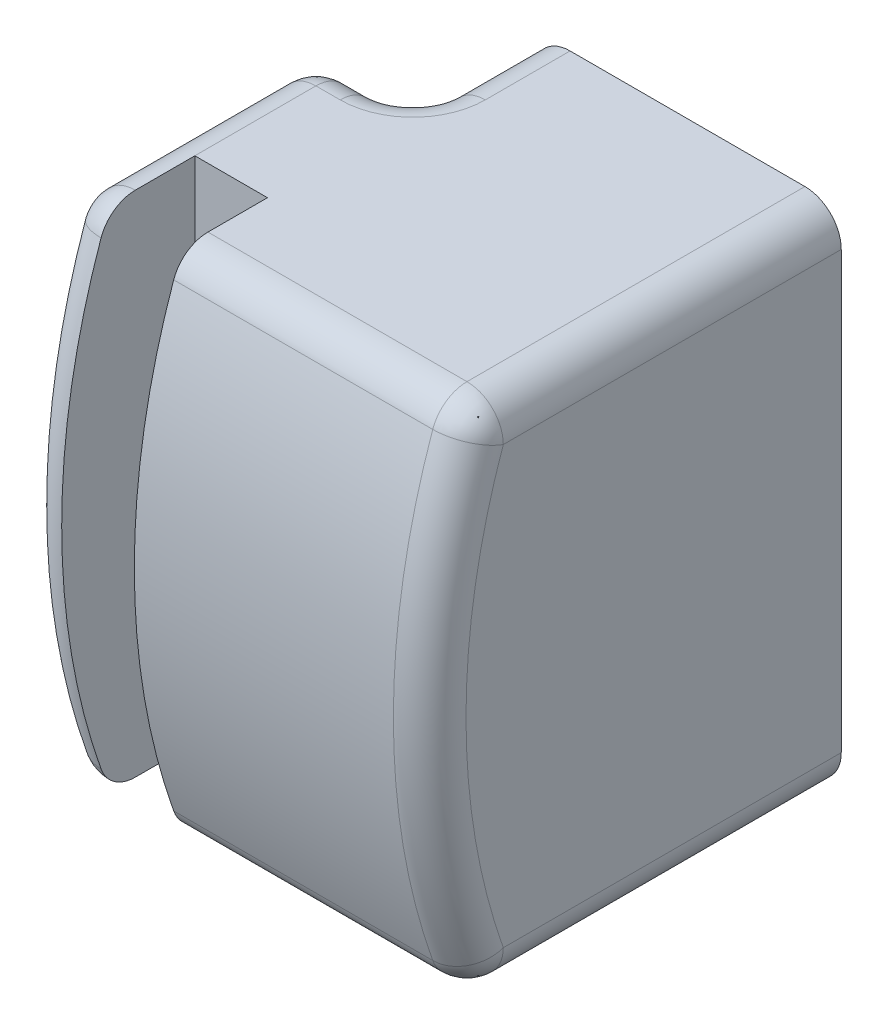
SolidWorks part; units mm, degrees
ref_plane "Alzado" through (0, 0, 0) normal (0, 0, 1) x (1, 0, 0)
ref_plane "Planta" through (0, 0, 0) normal (0, 1, 0) x (1, 0, 0)
ref_plane "Vista lateral" through (0, 0, 0) normal (1, 0, 0) x (0, 0, -1)
sketch "Croquis1" plane through (0, 0, 0) normal (0, 0, 1) x (1, 0, 0)
  line L1 (-58.5, 100) -> (58.5, 100)
  line L2 (-58.5, 100) -> (-58.5, -100)
  line L3 (-58.5, -100) -> (58.5, -100)
  line L4 (58.5, 100) -> (58.5, -100)
  line L5 (-58.5, 100) -> (58.5, -100) construction
  line L6 (-58.5, -100) -> (58.5, 100) construction
  point P0 (0, 0)
  dimension "D1" = 200
  dimension "D2" = 117
extrude "Saliente-Extruir1" add sketch "Croquis1" along normal blind 5
sketch "Croquis2" plane through (0, 0, 5) normal (0, 0, 1) x (1, 0, 0)
  line L1 (-58.5, 100) -> (58.5, 100)
  line L2 (-58.5, 100) -> (-58.5, -100)
  line L3 (-58.5, -100) -> (58.5, -100)
  line L4 (58.5, 100) -> (58.5, -100)
  line L5 (-58.5, 100) -> (58.5, -100) construction
  line L6 (-58.5, -100) -> (58.5, 100) construction
  line L7 (-63.5, 105) -> (63.5, 105)
  line L8 (-63.5, 105) -> (-63.5, -105)
  line L9 (-63.5, -105) -> (63.5, -105)
  line L10 (63.5, 105) -> (63.5, -105)
  line L11 (-63.5, 105) -> (63.5, -105) construction
  line L12 (-63.5, -105) -> (63.5, 105) construction
  point P0 (0, 0)
  point P7 (0, 0)
  dimension "D1" = 5
  dimension "D2" = 5
extrude "Saliente-Extruir2" add sketch "Croquis2" against normal blind 150
sketch "Croquis3" plane through (-63.5, 0, 0) normal (-1, 0, 0) x (0, 0, 1)
  line L0 (5, 105) -> (5, -105)
  line L1 (5, -105) -> (-95, -105)
  line L2 (-145, -105) -> (5, -105) construction
  line L3 (-95, -105) -> (-95, 105)
  line L4 (-145, 105) -> (5, 105) construction
  line L5 (-95, 105) -> (5, 105)
  dimension "D1" = 100
extrude "Saliente-Extruir3" add sketch "Croquis3" along normal blind 40
sketch "Croquis4" plane through (-103.5, 0, 0) normal (-1, 0, 0) x (0, 0, 1)
  line L0 (5, 105) -> (5, -105)
  arc A0 (5, -105) -> (5, 105) centre (-260.625, 0) ccw
  point P2 (25, 0)
  point P6 (5, 0)
  dimension "D1" = 20
extrude "Saliente-Extruir4" add sketch "Croquis4" against normal up to surface (167 mm away) up to face at (63.5, 0, -70)
fillet "Redondeo1" radius 15 14 edges at (63.5, -105, -70) (-63.5, 0, -95) (-63.5, -105, -120) (-83.5, -105, -95) (-63.5, 105, -120) (-83.5, 105, -95) (-103.5, 0, -95) (-103.5, -105, -45) (-20, -105, 5) (63.5, 0, 25) (-103.5, 0, 25) (-103.5, 105, -45) (63.5, 105, -70) (-20, 105, 5)
sketch "Croquis5" plane through (0, 0, 0) normal (0, 0, 1) x (1, 0, 0)
  line L0 (-88.5, 105) -> (-88.5, -105)
  line L1 (-88.5, -105) -> (-58.5, -105)
  line L2 (-58.5, -105) -> (-58.5, 105)
  line L3 (-88.5, 105) -> (48.5, 105) construction
  line L4 (-58.5, 105) -> (-88.5, 105)
  dimension "D1" = 30
extrude "Cortar-Extruir1" cut sketch "Croquis5" against normal blind 30 and the other way through all
sketch "Croquis6" plane through (-58.5, 0, 0) normal (-1, 0, 0) x (0, 0, 1)
  line L0 (-5.4037, -105) -> (-5.4037, -89.5) construction
  line L1 (-5.4037, -89.5) -> (-7.4037, -89.5) construction
  line L2 (-7.4037, -89.5) -> (-7.4037, -40.5) construction
  line L3 (0, -36.1809) -> (-12.5, -36.1809)
  line L4 (0, 100) -> (0, -100) construction
  line L5 (-12.5, -36.1809) -> (-12.5, -44.6528)
  line L6 (-12.5, -44.6528) -> (0, -44.6528)
  line L7 (0, -44.6528) -> (0, -36.1809)
  line L8 (-7.4037, -65) -> (-2.6004, -65) construction
  line L9 (-12.5, -93.8191) -> (-12.5, -85.3472)
  line L10 (0, -93.8191) -> (-12.5, -93.8191)
  line L11 (0, -85.3472) -> (0, -93.8191)
  line L12 (-12.5, -85.3472) -> (0, -85.3472)
  circle A0 centre (-7.4037, -89.5) radius 2.5
  circle A1 centre (-7.4037, -40.5) radius 2.5
  dimension "D3" = 5
  dimension "D1" = 15.5
  dimension "D2" = 2
  dimension "D4" = 49
  dimension "D5" = 12.5
extrude "Saliente-Extruir6" add sketch "Croquis6" against normal blind 2
